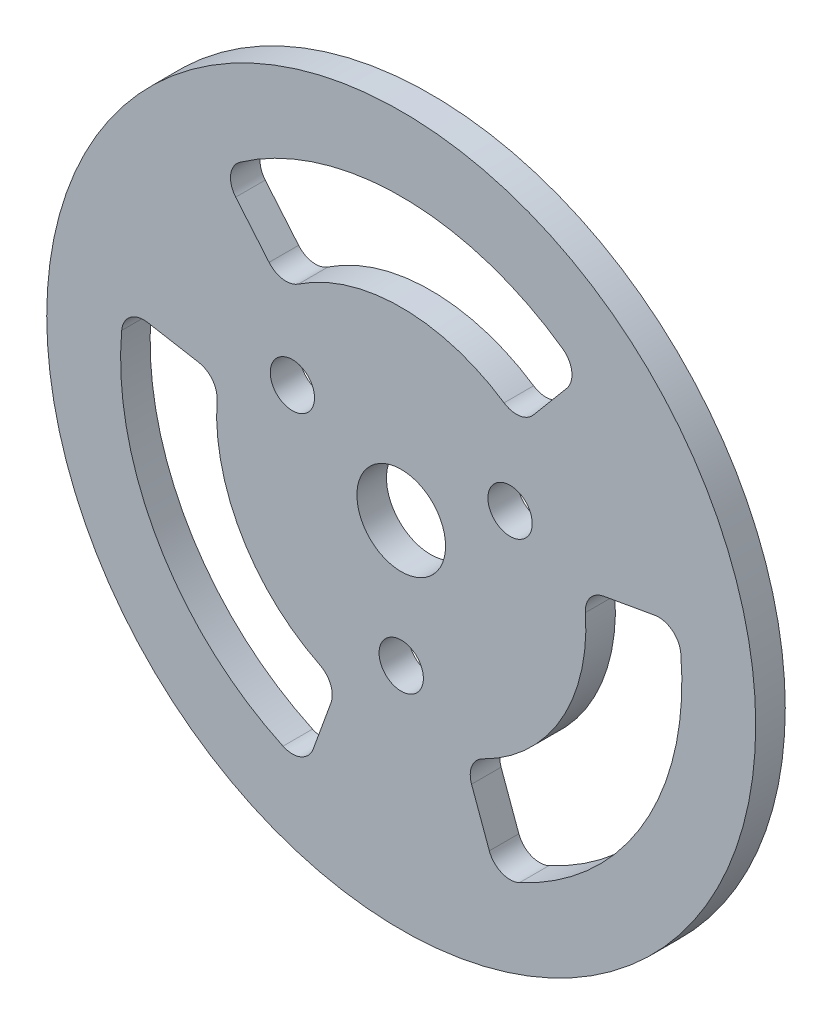
SolidWorks part; units mm, degrees
ref_plane "前视基准面" through (0, 0, 0) normal (0, 0, 1) x (1, 0, 0)
ref_plane "上视基准面" through (0, 0, 0) normal (0, 1, 0) x (1, 0, 0)
ref_plane "右视基准面" through (0, 0, 0) normal (1, 0, 0) x (0, 0, -1)
sketch "草图1" plane through (0, 0, 0) normal (0, 0, 1) x (1, 0, 0)
  line L1 (8.0348, 9.5756) -> (12.213, 14.5548)
  line L2 (12.3101, 2.1706) -> (18.7113, 3.2993)
  line L4 (4.2753, -11.7462) -> (6.4984, -17.8542)
  line L5 (-4.2753, -11.7462) -> (-6.4984, -17.8542)
  line L7 (-12.3101, 2.1706) -> (-18.7113, 3.2993)
  line L8 (-8.0348, 9.5756) -> (-12.213, 14.5548)
  circle A0 centre (0, 0) radius 24
  arc A1 (-18.7113, 3.2993) -> (-6.4984, -17.8542) centre (0, 0) ccw
  arc A2 (-12.3101, 2.1706) -> (-4.2753, -11.7462) centre (0, 0) ccw
  arc A3 (6.4984, -17.8542) -> (18.7113, 3.2993) centre (0, 0) ccw
  arc A4 (4.2753, -11.7462) -> (12.3101, 2.1706) centre (0, 0) ccw
  arc A5 (8.0348, 9.5756) -> (-8.0348, 9.5756) centre (0, 0) ccw
  arc A6 (12.213, 14.5548) -> (-12.213, 14.5548) centre (0, 0) ccw
  circle A7 centre (0, 0) radius 3
  circle A10 centre (-7.3684, 4.2542) radius 1.5
  circle A11 centre (7.3684, 4.2542) radius 1.5
  circle A12 centre (0, -8.5083) radius 1.5
  point P25 (0, 0)
  point P28 (0, 0)
  dimension "D1" = 3
extrude "凸台-拉伸1" add sketch "草图1" along normal blind 2
fillet "圆角1" radius 1.5 12 edges at (-6.4984, -17.8542, 1) (-4.2753, -11.7462, 1) (-12.3101, 2.1706, 1) (-18.7113, 3.2993, 1) (12.3101, 2.1706, 1) (18.7113, 3.2993, 1) (6.4984, -17.8542, 1) (4.2753, -11.7462, 1) (-12.213, 14.5548, 1) (-8.0348, 9.5756, 1) (8.0348, 9.5756, 1) (12.213, 14.5548, 1)
